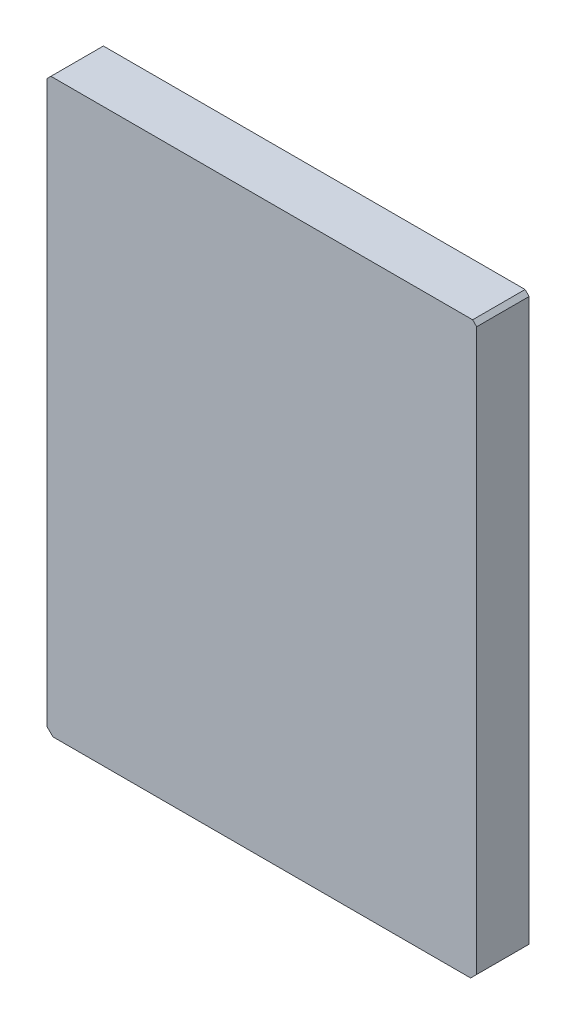
SolidWorks part; units mm, degrees
ref_plane "Front Plane" through (0, 0, 0) normal (0, 0, 1) x (1, 0, 0)
ref_plane "Top Plane" through (0, 0, 0) normal (0, 1, 0) x (1, 0, 0)
ref_plane "Right Plane" through (0, 0, 0) normal (1, 0, 0) x (0, 0, -1)
sketch "Sketch1" plane through (0, 0, 0) normal (0, 0, 1) x (1, 0, 0)
  line L0 (0, 0) -> (100.5, 0)
  line L5 (0, -134.5) -> (100.5, -134.5)
  line L6 (50.25, 0) -> (50.25, -201.1708) construction
  line L7 (0, 0) -> (0, -134.5)
  line L8 (100.5, 0) -> (100.5, -134.5)
  point P8 (50.25, -134.5)
  dimension "D1" = 100.5
  dimension "D2" = 100.5
  dimension "D3" = 134.5
extrude "Boss-Extrude1" add sketch "Sketch1" along normal blind 2
sketch "Sketch2" plane through (0, 0, 2) normal (0, 0, 1) x (1, 0, 0)
  line L0 (102.5, 2) -> (-2, 2)
  line L1 (-2, 2) -> (-2, -136.5)
  line L2 (-2, -136.5) -> (102.5, -136.5)
  line L3 (102.5, -136.5) -> (102.5, 2)
  line L4 (0, 0) -> (0, -134.5)
  line L5 (0, -134.5) -> (100.5, -134.5)
  line L6 (100.5, -134.5) -> (100.5, 0)
  line L7 (100.5, 0) -> (0, 0)
  line L8 (0, 0) -> (0, -134.5)
  line L9 (0, -134.5) -> (100.5, -134.5)
  line L10 (100.5, -134.5) -> (100.5, 0)
  line L11 (100.5, 0) -> (0, 0)
  dimension "D1" = 0
  dimension "D2" = 2
extrude "Boss-Extrude2" add sketch "Sketch2" against normal blind 13
sketch "Sketch3" plane through (0, 0, 0) normal (0, 0, -1) x (-1, 0, 0)
  line L0 (-50.25, 0) -> (-50.25, -72) construction
  line L1 (-100.5, 0) -> (0, 0) construction
  line L2 (-101.125, -72) -> (0.625, -72) construction
  line L5 (-52.25, 0) -> (-52.25, -70)
  line L6 (-101.125, -70) -> (-101.125, -74)
  line L7 (0.625, -70) -> (0.625, -74)
  line L8 (-52.25, 0) -> (-48.25, 0)
  line L10 (-48.25, 0) -> (-48.25, -70)
  line L11 (-101.125, -74) -> (0.625, -74)
  line L12 (-101.125, -70) -> (-52.25, -70)
  line L13 (-48.25, -70) -> (0.625, -70)
  line L15 (-101.125, -70) -> (0.625, -70) construction
  line L16 (-52.25, 0) -> (-52.25, -72) construction
  line L17 (-48.25, 0) -> (-48.25, -72) construction
  dimension "D5" = 72
  dimension "D1" = 2
  dimension "D2" = 2
  dimension "D3" = 2
  dimension "D4" = 2
extrude "Boss-Extrude3" add sketch "Sketch3" along normal blind 2 contours L11 L7 L13 L10 L8 L5 L12 L6
sketch "Sketch5" plane through (0, -136.5, 0) normal (0, -1, 0) x (1, 0, 0)
  line L1 (102.5, 2) -> (-2, 2)
  line L2 (102.5, 2) -> (102.5, -11)
  line L3 (102.5, -11) -> (-2, -11)
  line L4 (-2, 2) -> (-2, -11)
extrude "Boss-Extrude4" add sketch "Sketch5" along normal blind 2
sketch "Sketch4" plane through (0, -138.5, 0) normal (0, -1, 0) x (1, 0, 0)
  line L0 (0, 0) -> (100.5, 0) construction
  line L1 (87.75, -8.25) -> (12.75, -8.25) construction
  line L2 (89.65, -8.25) -> (89.65, -11)
  line L4 (-2, -11) -> (102.5, -11) construction
  line L5 (89.65, -11) -> (85.85, -11)
  line L6 (85.85, -11) -> (85.85, -8.25)
  line L7 (14.65, -8.25) -> (14.65, -11)
  line L8 (14.65, -11) -> (10.85, -11)
  line L9 (10.85, -11) -> (10.85, -8.25)
  line L10 (50.25, -11) -> (50.25, -3.065) construction
  arc A0 (89.65, -8.25) -> (85.85, -8.25) centre (87.75, -8.25) ccw
  arc A1 (14.65, -8.25) -> (10.85, -8.25) centre (12.75, -8.25) ccw
  point P10 (50.25, -8.25)
  dimension "D1" = 3.8
  dimension "D2" = 3.8
  dimension "D3" = 75
  dimension "D4" = 8.25
extrude "Cut-Extrude2" cut sketch "Sketch4" against normal blind 2
sketch "Sketch8" plane through (0, 0, 0) normal (0, 0, -1) x (-1, 0, 0)
  line L0 (0, -134.5) -> (-100.5, -134.5) construction
  line L1 (-10.25, -120.5) -> (-15.25, -120.5)
  line L2 (-10.25, -120.5) -> (-10.25, -116.5)
  line L3 (-10.25, -116.5) -> (-15.25, -116.5)
  line L4 (-15.25, -120.5) -> (-15.25, -116.5)
  line L5 (-85.25, -120.5) -> (-90.25, -120.5)
  line L6 (-85.25, -120.5) -> (-85.25, -116.5)
  line L7 (-85.25, -116.5) -> (-90.25, -116.5)
  line L8 (-90.25, -120.5) -> (-90.25, -116.5)
  line L10 (-48.25, 0) -> (-48.25, -70) construction
  line L11 (-52.25, 0) -> (-52.25, -70) construction
  line L12 (0, -134.5) -> (-100.5, -134.5) construction
  dimension "D1" = 14
  dimension "D2" = 4
  dimension "D3" = 4
  dimension "D4" = 5
  dimension "D5" = 33
  dimension "D6" = 33
  dimension "D7" = 14
extrude "Boss-Extrude5" add sketch "Sketch8" along normal blind 12
fillet "Fillet1" radius 4 8 edges at (87.75, -120.5, 0) (12.75, -120.5, 0) (87.75, -116.5, 0) (12.75, -116.5, 0) (10.25, -118.5, 0) (15.25, -118.5, 0) (90.25, -118.5, 0) (85.25, -118.5, 0)
sketch "Sketch7" plane through (0, -136.5, 0) normal (0, -1, 0) x (1, 0, 0)
  line L0 (88.75, -8.25) -> (88.75, -11)
  line L1 (85.85, -11) -> (89.65, -11) construction
  line L2 (88.75, -11) -> (86.75, -11)
  line L3 (86.75, -11) -> (86.75, -8.25)
  line L4 (13.75, -8.25) -> (13.75, -11)
  line L5 (10.85, -11) -> (14.65, -11) construction
  line L6 (13.75, -11) -> (11.75, -11)
  line L7 (11.75, -11) -> (11.75, -8.25)
  arc A0 (88.75, -8.25) -> (86.75, -8.25) centre (87.75, -8.25) ccw
  arc A1 (13.75, -8.25) -> (11.75, -8.25) centre (12.75, -8.25) ccw
  dimension "D1" = 2
extrude "Cut-Extrude3" cut sketch "Sketch7" against normal blind 20
sketch "Sketch13" plane through (0, 0, -11) normal (0, 0, -1) x (-1, 0, 0)
  line L0 (2, 2) -> (3, 2) construction
  line L1 (2, -138.5) -> (3, -138.5)
  line L2 (3, 2) -> (3, -138.5)
  line L3 (2, -138.5) -> (2, 2)
  line L4 (-50.25, 2) -> (-50.25, -5.5454) construction
  line L5 (-102.5, 2) -> (2, 2) construction
  line L6 (-102.5, -138.5) -> (-102.5, 2)
  line L7 (-103.5, 2) -> (-103.5, -138.5)
  line L8 (-102.5, -138.5) -> (-103.5, -138.5)
  line L9 (-102.5, 2) -> (-103.5, 2) construction
  line L10 (-102.5, 2) -> (-102.5, 3) construction
  line L11 (-102.5, 3) -> (2, 3)
  line L12 (2, 2) -> (2, 3) construction
  line L13 (-103.5, 2) -> (-102.5, 3)
  line L14 (3, 2) -> (2, 3)
  line L15 (-102.5, 2) -> (2, 2)
  dimension "D1" = 1
  dimension "D2" = 1
extrude "Boss-Extrude7" add sketch "Sketch13" against normal up to surface (13 mm away) up to face at (50.25, -68.25, 2)
chamfer "Chamfer1" distance 1.5 angle 45 2 edges at (-3, -138.5, -4.5) (103.5, -138.5, -4.5)
fillet "Fillet2" radius 1 5 edges at (24.125, -70, 0) (76.375, -70, 0) (52.25, -35, 0) (48.25, -35, 0) (50.25, -74, 0)
